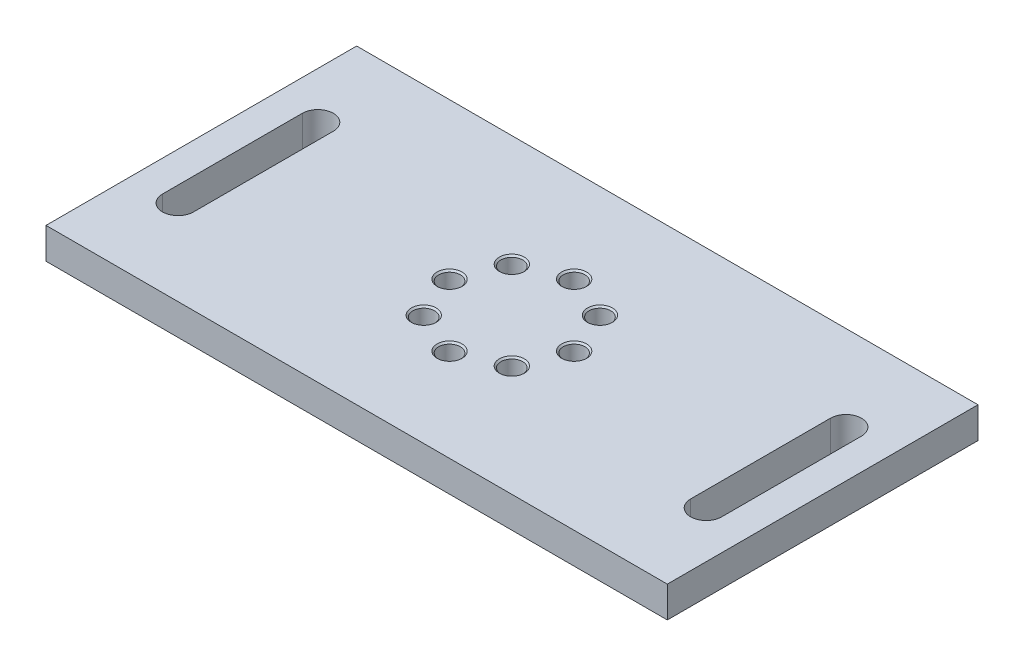
SolidWorks part; units mm, degrees
ref_plane "Front Plane" through (0, 0, 0) normal (0, 0, 1) x (1, 0, 0)
ref_plane "Top Plane" through (0, 0, 0) normal (0, 1, 0) x (1, 0, 0)
ref_plane "Right Plane" through (0, 0, 0) normal (1, 0, 0) x (0, 0, -1)
sketch "Sketch2" plane through (0, 0, 0) normal (0, 1, 0) x (1, 0, 0)
  line L1 (0, 0) -> (200, 0)
  line L2 (0, 0) -> (0, 100)
  line L3 (0, 100) -> (200, 100)
  line L4 (200, 0) -> (200, 100)
  dimension "D1" = 200
  dimension "D2" = 100
extrude "Boss-Extrude2" add sketch "Sketch2" along normal blind 10
sketch "Sketch3" plane through (0, 10, 0) normal (0, 1, 0) x (1, 0, 0)
  line L0 (0, 50) -> (200, 50) construction
  line L1 (0, 100) -> (0, 0) construction
  line L2 (200, 0) -> (200, 100) construction
  line L3 (100, 100) -> (100, 0) construction
  line L4 (200, 100) -> (0, 100) construction
  line L5 (0, 0) -> (200, 0) construction
  point P12 (100, 70)
  dimension "D1" = 20
hole_wizard "M8x1.0 Tapped Hole1" positions "Sketch4" profile "Sketch5" tap size "M8x1.0" standard "ANSI Metric" end condition through all
sketch "Sketch4" plane through (0, 10, 0) normal (0, 1, 0) x (1, 0, 0)
  point P0 (100, 70)
sketch "Sketch5" plane through (100, 10, -70) normal (1, 0, 0) x (0, 0, 1)
  line L0 (0, 0) -> (0, 10)
  line L1 (0, 10) -> (3.5, 10)
  line L2 (3.5, 10) -> (3.5, 0.525)
  line L3 (3.5, 0.525) -> (4.025, 0)
  line L5 (4.025, 0) -> (0, 0)
  line L6 (-3.5, 0.525) -> (-4.025, 0) construction
  line L11 (0, -6.35) -> (0, 107.95) construction
  dimension "Thru Tap Drill Dia." = 7
  dimension "Thru Tap Drill Depth" = 10
  dimension "Near C'Sink Dia." = 8.05
  dimension "Near C'Sink Angle" = 90
cosmetic thread "Hole Thread1" parameters "D2"=8
pattern_circular "CirPattern1" count 8 over 360 about axis through (100, 0, -49.949) along (0, 1, 0) of "M8x1.0 Tapped Hole1"
sketch "Sketch6" plane through (0, 10, 0) normal (0, 1, 0) x (1, 0, 0)
  line L0 (15, 72.5) -> (15, 27.5) construction
  line L1 (20, 72.5) -> (20, 27.5)
  line L2 (10, 72.5) -> (10, 27.5)
  line L3 (0, 100) -> (0, 0) construction
  line L5 (0, 50) -> (200, 50) construction
  line L6 (100, 100) -> (100, 0) construction
  line L7 (185, 72.5) -> (185, 27.5) construction
  line L8 (180, 72.5) -> (180, 27.5)
  line L9 (190, 72.5) -> (190, 27.5)
  arc A0 (20, 72.5) -> (10, 72.5) centre (15, 72.5) ccw
  arc A1 (10, 27.5) -> (20, 27.5) centre (15, 27.5) ccw
  arc A2 (180, 72.5) -> (190, 72.5) centre (185, 72.5) cw
  arc A3 (190, 27.5) -> (180, 27.5) centre (185, 27.5) cw
  point P2 (15, 50)
  point P17 (185, 50)
  dimension "D1" = 5
  dimension "D2" = 45
  dimension "D3" = 15
extrude "Cut-Extrude1" cut sketch "Sketch6" against normal through all
